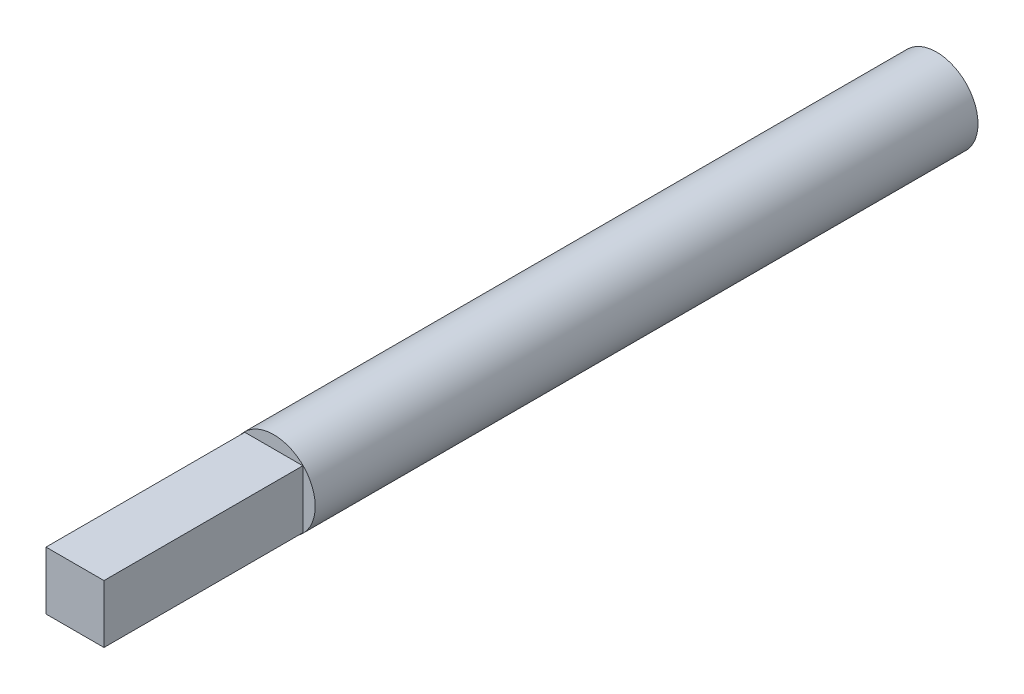
SolidWorks part; units mm, degrees
ref_plane "Front Plane" through (0, 0, 0) normal (0, 0, 1) x (1, 0, 0)
ref_plane "Top Plane" through (0, 0, 0) normal (0, 1, 0) x (1, 0, 0)
ref_plane "Right Plane" through (0, 0, 0) normal (1, 0, 0) x (0, 0, -1)
sketch "Sketch1" plane through (0, 0, 0) normal (0, 0, 1) x (1, 0, 0)
  circle A0 centre (0, 0) radius 1.25
  dimension "D1" = 2.5
extrude "Boss-Extrude1" add sketch "Sketch1" along normal blind 5
sketch "Sketch2" plane through (0, 0, 5) normal (0, 0, 1) x (1, 0, 0)
  line L1 (-0.875, -0.875) -> (0.875, -0.875)
  line L2 (-0.875, -0.875) -> (-0.875, 0.875)
  line L3 (-0.875, 0.875) -> (0.875, 0.875)
  line L4 (0.875, -0.875) -> (0.875, 0.875)
  line L5 (-0.875, -0.875) -> (0.875, 0.875) construction
  line L6 (-0.875, 0.875) -> (0.875, -0.875) construction
  point P0 (0, 0)
  dimension "D1" = 1.75
  dimension "D2" = 1.75
extrude "Boss-Extrude2" add sketch "Sketch2" along normal blind 6
sketch "Sketch3" plane through (0, 0, 0) normal (0, 0, 1) x (1, 0, 0)
  circle A0 centre (0, 0) radius 1.25
  dimension "D1" = 2.5
extrude "Boss-Extrude3" add sketch "Sketch3" against normal blind 15
